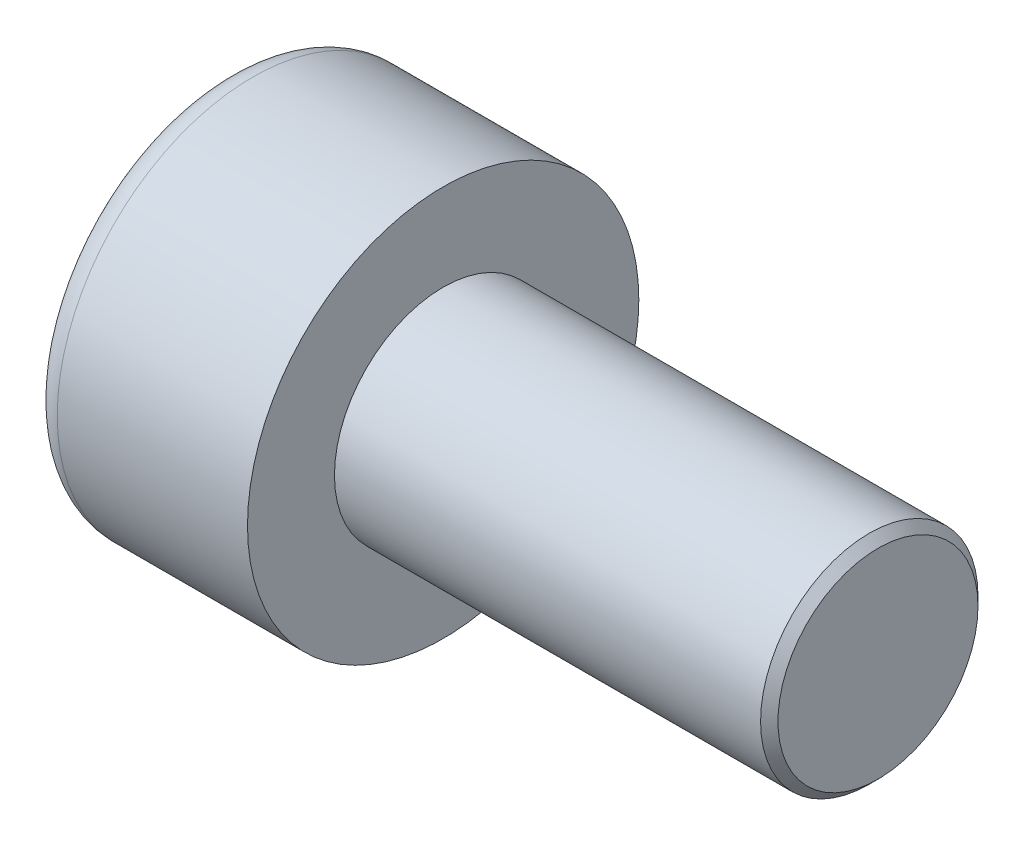
SolidWorks part; units mm, degrees
material "合金钢"
ref_plane "Front" through (0, 0, 0) normal (0, 0, 1) x (1, 0, 0)
ref_plane "Top" through (0, 0, 0) normal (0, 1, 0) x (1, 0, 0)
ref_plane "Right" through (0, 0, 0) normal (1, 0, 0) x (0, 0, -1)
sketch "Sketch1" plane through (0, 0, 0) normal (1, 0, 0) x (0, 0, -1)
  circle A0 centre (0, 0) radius 2.25
  dimension "dk" = 4.5
extrude "BaseHead" add sketch "Sketch1" along normal blind 2.5
sketch "Sketch2" plane through (2.5, 0, 0) normal (1, 0, 0) x (0, 0, -1)
  circle A0 centre (0, 0) radius 1.25
  dimension "d" = 2.5
extrude "BaseBody" add sketch "Sketch2" along normal blind 5
cosmetic thread "ThreadCosmetic1" [suppressed] parameters "b"=6, "D2"=2.013
sketch "Sketch3" plane through (0, 0, 0) normal (1, 0, 0) x (0, 0, -1)
  line L1 (1.1547, 0) -> (0.5774, 1)
  line L2 (0.5774, 1) -> (-0.5774, 1)
  line L3 (-0.5774, 1) -> (-1.1547, 0)
  line L4 (-1.1547, 0) -> (-0.5774, -1)
  line L5 (-0.5774, -1) -> (0.5774, -1)
  line L6 (0.5774, -1) -> (1.1547, 0)
  circle A0 centre (0, 0) radius 1 construction
  dimension "s" = 2
  dimension "e" = 2.3094
extrude "HexagonSocket" cut sketch "Sketch3" along normal blind 1.1
sketch "Sketch4" plane through (-4.1961, 0.75, 0) normal (0, 0, 1) x (-1, 0, 0)
  line L0 (-5.2961, 1.75) -> (-5.8735, 0.75)
  line L2 (-5.8735, 0.75) -> (-5.2961, 0.75)
  line L3 (-5.2961, 0.75) -> (-5.2961, 1.75)
  line L4 (-5.0351, 0.75) -> (0.839, 0.75) construction
  line L5 (-11.6961, 0.75) -> (-6.6961, 0.75) construction
  line L6 (-6.6961, 0.75) -> (-4.1961, 0.75) construction
  dimension "m" = 60
revolve "Cut-Revolve1" cut sketch "Sketch4" angle 360 about L4
fillet "HeadFillet" [suppressed] radius 0.1
fillet "TopFillet" radius 0.3125 1 edges at (0, 0, -2.25)
chamfer "Chamfer1" distance 0.1 angle 45 1 edges at (7.5, 0, -1.25)
sketch "Sketch5" plane through (0, 0, 0) normal (0, 0, 1) x (1, 0, 0)
  line L0 (7.4, 1.0391) -> (7.5217, 1.25)
  line L1 (7.5217, 1.25) -> (7.5217, 1.4935)
  line L2 (7.5217, 1.4935) -> (7.2782, 1.4935)
  line L3 (7.2782, 1.4935) -> (7.2782, 1.25)
  line L4 (7.2782, 1.25) -> (7.4, 1.0391)
  line L5 (0, 0) -> (7.8886, 0) construction
  line L6 (7.4, -1.25) -> (7.4, 1.25) construction
  dimension "D1" = 2.5
  dimension "D2" = 0.2435
revolve "Cut-Revolve10" [suppressed] cut sketch "Sketch5" angle 360 about L5
pattern_linear "LPattern10" [suppressed] count 21 spacing 0.2922 along (1, 0, 0)
equation "\"r1@TopFillet\" = \"d@Sketch2\" / 8"
equation "\"D1@Chamfer1\" = \"r@HeadFillet\""
equation "\"D1@Sketch5\" = \"d@Sketch2\""
equation "\"D2@Sketch5\" =  ( \"d@Sketch2\" - \"D2@ThreadCosmetic1\" )  / 2"
equation "\"D3@LPattern10\" = \"D2@Sketch5\" * 1.2"
equation "\"D1@LPattern10\" = \"b@ThreadCosmetic1\" / \"D3@LPattern10\""
